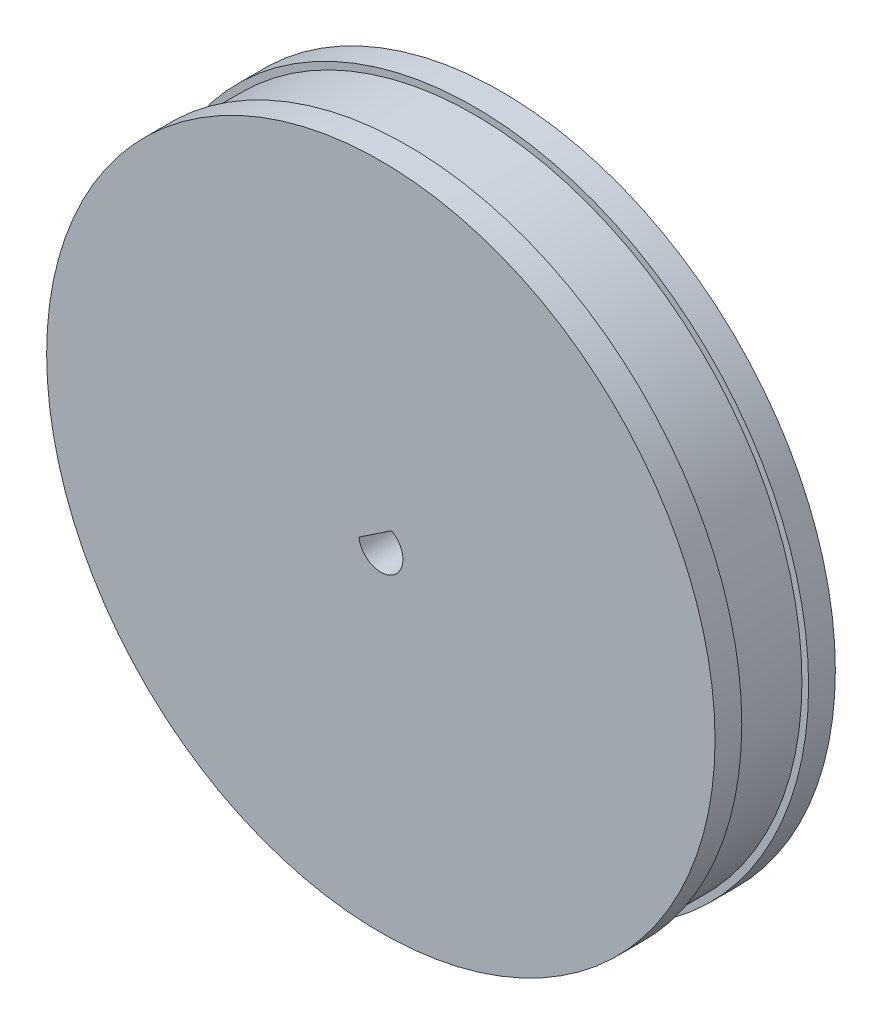
SolidWorks part; units mm, degrees
ref_plane "Plan de face" through (0, 0, 0) normal (0, 0, 1) x (1, 0, 0)
ref_plane "Plan de dessus" through (0, 0, 0) normal (0, 1, 0) x (1, 0, 0)
ref_plane "Plan de droite" through (0, 0, 0) normal (1, 0, 0) x (0, 0, -1)
sketch "Esquisse1" plane through (0, 0, 0) normal (0, 0, 1) x (1, 0, 0)
  circle A0 centre (0, 0) radius 25
  circle A1 centre (0, 0) radius 24.5
  dimension "D1" = 50
  dimension "D2" = 49
extrude "Boss.-Extru.1" add sketch "Esquisse1" along normal blind 5 contours A1
sketch "Esquisse2" plane through (0, 0, 0) normal (0, 0, -1) x (-1, 0, 0)
  circle A0 centre (0, 0) radius 25
  dimension "D1" = 50
extrude "Boss.-Extru.2" add sketch "Esquisse2" along normal blind 2
sketch "Esquisse3" plane through (0, 0, 5) normal (0, 0, 1) x (1, 0, 0)
  circle A0 centre (0, 0.5386) radius 25
  dimension "D1" = 50
extrude "Boss.-Extru.3" [suppressed] add sketch "Esquisse3" along normal blind 2
sketch "Esquisse4" plane through (0, 0, -2) normal (0, 0, -1) x (-1, 0, 0)
  line L0 (1.2422, 1.086) -> (-1.2422, 1.086)
  circle A0 centre (0, 0) radius 1.65
  dimension "D1" = 3.3
sketch "Esquisse5" plane through (0, 0, 5) normal (0, 0, 1) x (1, 0, 0)
  circle A0 centre (0, 0) radius 25
  dimension "D1" = 50
extrude "Boss.-Extru.4" add sketch "Esquisse5" along normal blind 2
extrude "Enlèv. mat.-Extru.1" cut sketch "Esquisse4" against normal through all contours A0
sketch "Esquisse6" plane through (0, 0, 7) normal (0, 0, 1) x (1, 0, 0)
  line L0 (-1.6384, -0.195) -> (0.8035, 1.4411)
  circle A0 centre (0, 0) radius 1.65 construction
  arc A1 (0.8035, 1.4411) -> (-1.6384, -0.195) centre (0, 0) ccw
  dimension "D1" = 0.75
extrude "Boss.-Extru.5" add sketch "Esquisse6" against normal through all
